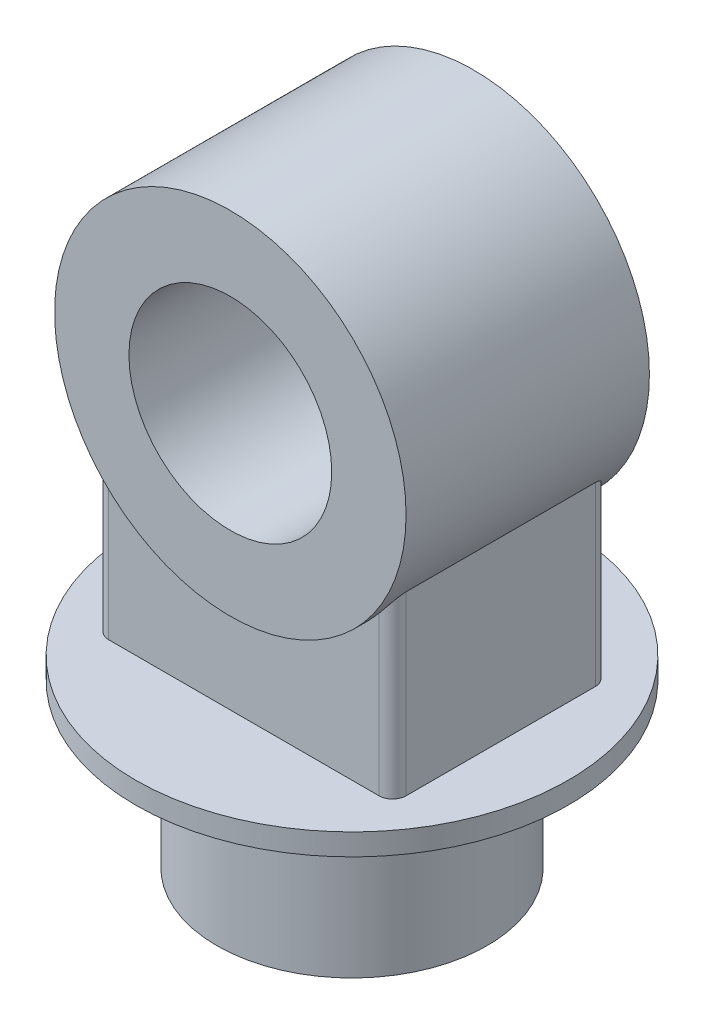
SolidWorks part; units mm, degrees
ref_plane "Alzado" through (0, 0, 0) normal (0, 0, 1) x (1, 0, 0)
ref_plane "Planta" through (0, 0, 0) normal (0, 1, 0) x (1, 0, 0)
ref_plane "Vista lateral" through (0, 0, 0) normal (1, 0, 0) x (0, 0, -1)
sketch "Croquis1" plane through (0, 0, 0) normal (0, 1, 0) x (1, 0, 0)
  circle A0 centre (0, 0) radius 100
  dimension "D1" = 200
extrude "Saliente-Extruir1" add sketch "Croquis1" along normal blind 120
sketch "Croquis2" plane through (0, 120, 0) normal (0, 1, 0) x (1, 0, 0)
  circle A0 centre (0, 0) radius 160
  dimension "D1" = 320
extrude "Saliente-Extruir2" add sketch "Croquis2" along normal blind 16
sketch "Croquis4" plane through (0, 0, 0) normal (0, 0, 1) x (1, 0, 0)
  line L0 (0, 142.0278) -> (0, 336) construction
  line L1 (160, 136) -> (-160, 136) construction
  circle A0 centre (0, 336) radius 130
  circle A1 centre (0, 336) radius 75
  dimension "D1" = 150
  dimension "D2" = 260
  dimension "D3" = 200
extrude "Saliente-Extruir3" add sketch "Croquis4" along normal mid plane 180 separate body contours A0 | A1
sketch "Croquis6" plane through (0, 136, 0) normal (0, 1, 0) x (1, 0, 0)
  line L1 (-110, -80) -> (110, -80)
  line L2 (-110, -80) -> (-110, 80)
  line L3 (-110, 80) -> (110, 80)
  line L4 (110, -80) -> (110, 80)
  line L5 (-110, -80) -> (110, 80) construction
  line L6 (-110, 80) -> (110, -80) construction
  point P0 (0, 0)
  dimension "D1" = 160
  dimension "D2" = 220
extrude "Saliente-Extruir4" add sketch "Croquis6" along normal up to next
fillet "Redondeo1" radius 10 4 edges at (110, 201.359, -80) (110, 201.359, 80) (-110, 201.359, -80) (-110, 201.359, 80)
